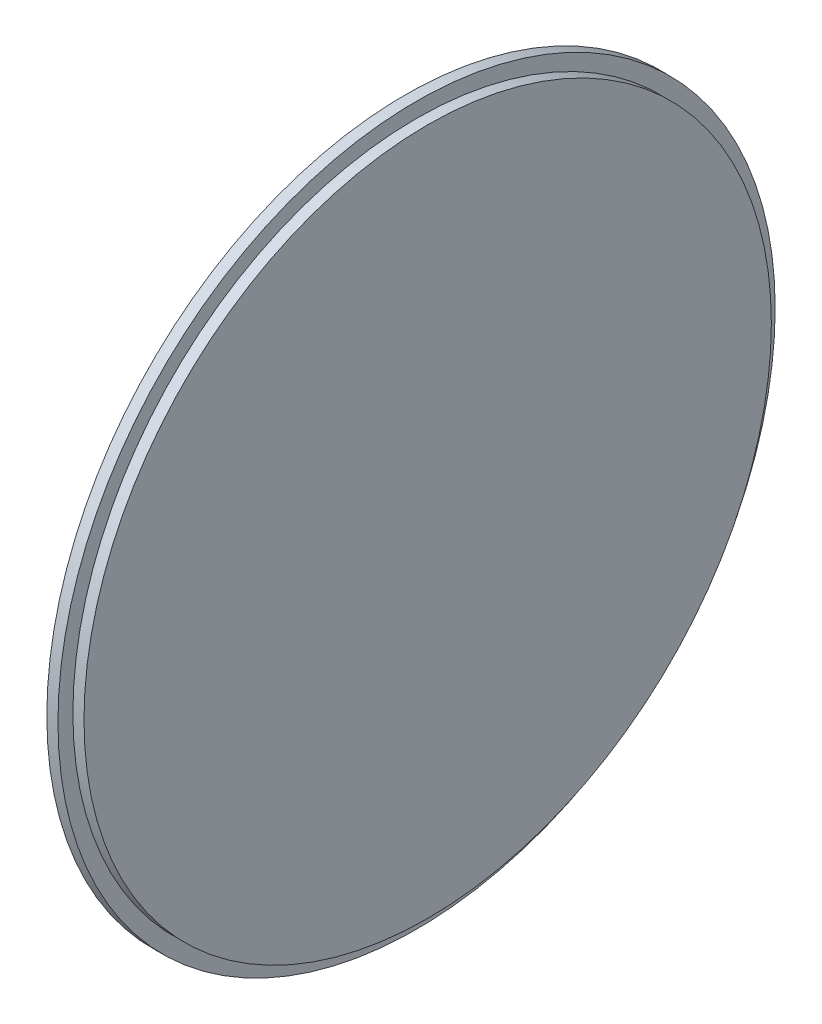
SolidWorks part; units mm, degrees
ref_plane "Front Plane" through (0, 0, 0) normal (1, 0, 0) x (0, 1, 0)
ref_plane "Top Plane" through (0, 0, 0) normal (0, 0, 1) x (0, 1, 0)
ref_plane "Right Plane" through (0, 0, 0) normal (0, 1, 0) x (-1, 0, 0)
sketch "Sketch1" plane through (0, 0, 0) normal (1, 0, 0) x (0, 1, 0)
  circle A0 centre (0, 0) radius 38.1
  dimension "D1" = 76.2
extrude "Boss-Extrude1" add sketch "Sketch1" along normal blind 1.1811
sketch "Sketch2" plane through (1.1811, 0, 0) normal (1, 0, 0) x (0, 1, 0)
  circle A0 centre (0, 0) radius 36.5125
  dimension "D1" = 73.025
extrude "Boss-Extrude2" add sketch "Sketch2" along normal blind 1.1811
